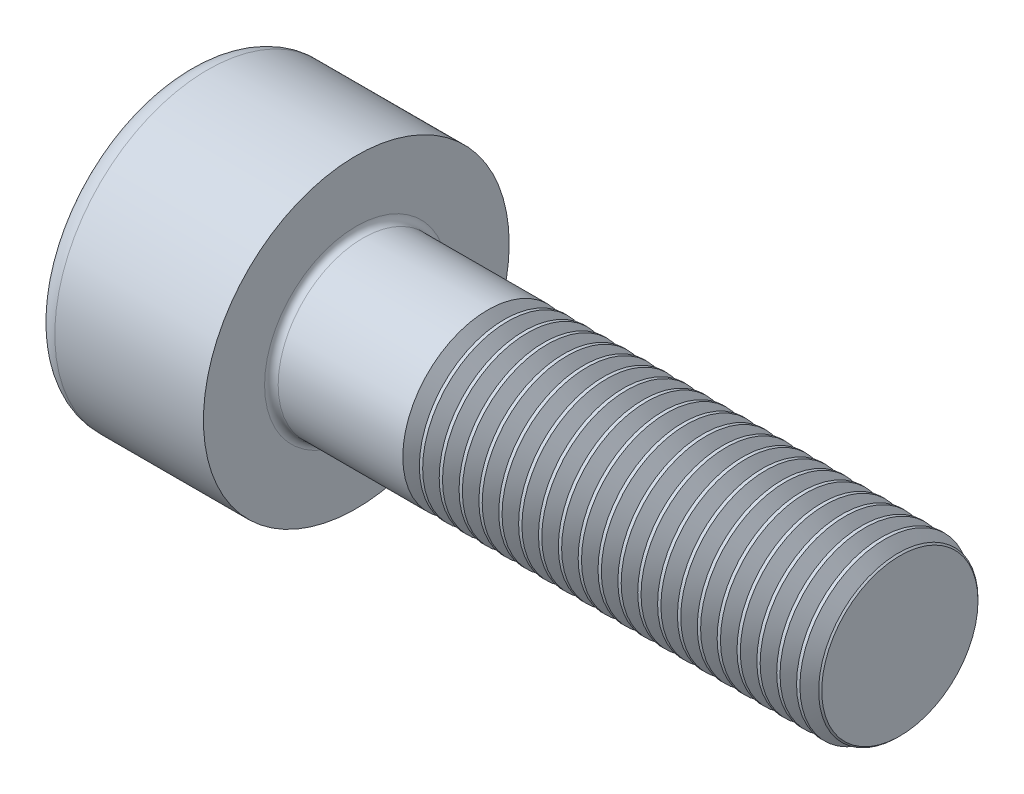
SolidWorks part; units mm, degrees
material "合金钢"
ref_plane "Front" through (0, 0, 0) normal (0, 0, 1) x (1, 0, 0)
ref_plane "Top" through (0, 0, 0) normal (0, 1, 0) x (1, 0, 0)
ref_plane "Right" through (0, 0, 0) normal (1, 0, 0) x (0, 0, -1)
sketch "Sketch1" plane through (0, 0, 0) normal (1, 0, 0) x (0, 0, -1)
  circle A0 centre (0, 0) radius 2.25
  dimension "dk" = 4.5
extrude "BaseHead" add sketch "Sketch1" along normal blind 2.5
sketch "Sketch2" plane through (2.5, 0, 0) normal (1, 0, 0) x (0, 0, -1)
  circle A0 centre (0, 0) radius 1.25
  dimension "d" = 2.5
extrude "BaseBody" add sketch "Sketch2" along normal blind 8
cosmetic thread "ThreadCosmetic1" [suppressed] parameters "b"=6, "D2"=2.013
sketch "Sketch3" plane through (0, 0, 0) normal (1, 0, 0) x (0, 0, -1)
  line L1 (1.1547, 0) -> (0.5774, 1)
  line L2 (0.5774, 1) -> (-0.5774, 1)
  line L3 (-0.5774, 1) -> (-1.1547, 0)
  line L4 (-1.1547, 0) -> (-0.5774, -1)
  line L5 (-0.5774, -1) -> (0.5774, -1)
  line L6 (0.5774, -1) -> (1.1547, 0)
  circle A0 centre (0, 0) radius 1 construction
  dimension "s" = 2
  dimension "e" = 2.3094
extrude "HexagonSocket" cut sketch "Sketch3" along normal blind 1.1
sketch "Sketch4" plane through (-4.1961, 0.75, 0) normal (0, 0, 1) x (-1, 0, 0)
  line L0 (-5.2961, 1.75) -> (-5.8735, 0.75)
  line L2 (-5.8735, 0.75) -> (-5.2961, 0.75)
  line L3 (-5.2961, 0.75) -> (-5.2961, 1.75)
  line L4 (-5.0351, 0.75) -> (0.839, 0.75) construction
  line L5 (-14.6961, 0.75) -> (-6.6961, 0.75) construction
  line L6 (-6.6961, 0.75) -> (-4.1961, 0.75) construction
  dimension "m" = 60
revolve "Cut-Revolve1" cut sketch "Sketch4" angle 360 about L4
fillet "HeadFillet" radius 0.1 1 edges at (2.5, 0, -1.25)
fillet "TopFillet" radius 0.3125 1 edges at (0, 0, -2.25)
chamfer "Chamfer1" distance 0.1 angle 45 1 edges at (10.5, 0, -1.25)
sketch "Sketch5" plane through (0, 0, 0) normal (0, 0, 1) x (1, 0, 0)
  line L0 (10.4, 1.0391) -> (10.5217, 1.25)
  line L1 (10.5217, 1.25) -> (10.5217, 1.4935)
  line L2 (10.5217, 1.4935) -> (10.2783, 1.4935)
  line L3 (10.2783, 1.4935) -> (10.2783, 1.25)
  line L4 (10.2783, 1.25) -> (10.4, 1.0391)
  line L5 (0, 0) -> (7.8886, 0) construction
  line L6 (10.4, -1.25) -> (10.4, 1.25) construction
  dimension "D1" = 2.5
  dimension "D2" = 0.2435
revolve "Cut-Revolve10" cut sketch "Sketch5" angle 360 about L5
pattern_linear "LPattern10" count 21 spacing 0.2922 along (-1, 0, 0) of "Cut-Revolve10"
equation "\"r1@TopFillet\" = \"d@Sketch2\" / 8"
equation "\"D1@Chamfer1\" = \"r@HeadFillet\""
equation "\"D1@Sketch5\" = \"d@Sketch2\""
equation "\"D2@Sketch5\" =  ( \"d@Sketch2\" - \"D2@ThreadCosmetic1\" )  / 2"
equation "\"D3@LPattern10\" = \"D2@Sketch5\" * 1.2"
equation "\"D1@LPattern10\" = \"b@ThreadCosmetic1\" / \"D3@LPattern10\""
